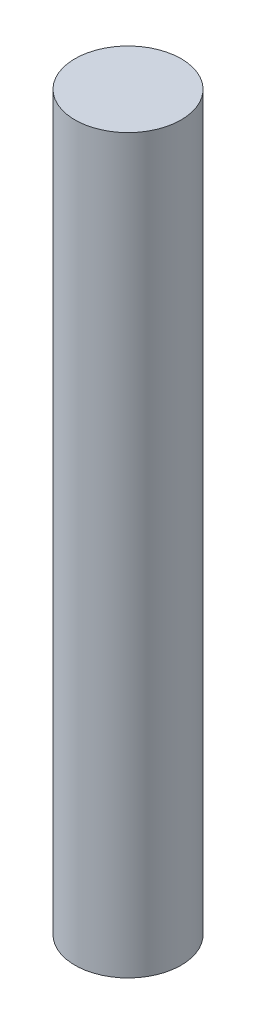
SolidWorks part; units mm, degrees
ref_plane "Front Plane" through (0, 0, 0) normal (0, 0, 1) x (1, 0, 0)
ref_plane "Top Plane" through (0, 0, 0) normal (0, 1, 0) x (1, 0, 0)
ref_plane "Right Plane" through (0, 0, 0) normal (1, 0, 0) x (0, 0, -1)
sketch "Sketch1" plane through (0, 0, 0) normal (0, 1, 0) x (1, 0, 0)
  circle A0 centre (0, 0) radius 1.8415
  dimension "D1" = 3.683
extrude "Boss-Extrude1" add sketch "Sketch1" along normal blind 25.4
